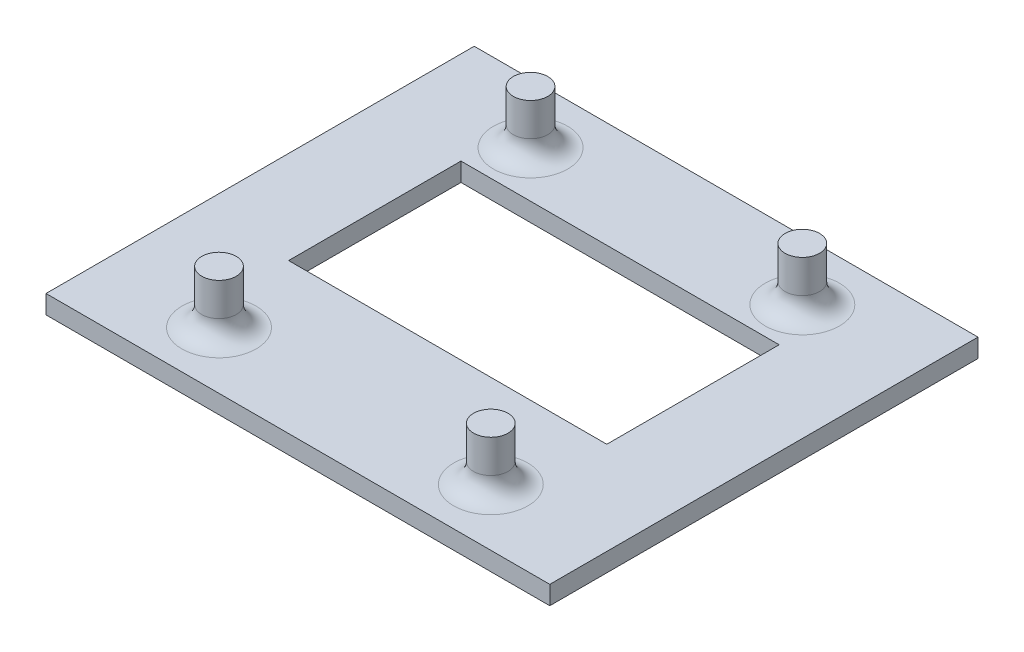
SolidWorks part; units mm, degrees
ref_plane "Front Plane" through (0, 0, 0) normal (0, 0, 1) x (1, 0, 0)
ref_plane "Top Plane" through (0, 0, 0) normal (0, 1, 0) x (1, 0, 0)
ref_plane "Right Plane" through (0, 0, 0) normal (1, 0, 0) x (0, 0, -1)
sketch "Sketch1" plane through (0, 0, 0) normal (0, 1, 0) x (1, 0, 0)
  line L0 (0, -55) -> (0, 55) construction
  line L1 (12, -6.5) -> (-12, -6.5)
  line L2 (12, -6.5) -> (12, 6.5)
  line L3 (12, 6.5) -> (-12, 6.5)
  line L4 (-12, -6.5) -> (-12, 6.5)
  line L5 (12, -6.5) -> (-12, 6.5) construction
  line L6 (12, 6.5) -> (-12, -6.5) construction
  line L7 (19, -17.8) -> (-19, -17.8)
  line L8 (19, -17.8) -> (19, 14.5)
  line L9 (19, 14.5) -> (-19, 14.5)
  line L10 (-19, -17.8) -> (-19, 14.5)
  line L11 (19, -17.8) -> (-19, 14.5) construction
  line L12 (19, 14.5) -> (-19, -17.8) construction
  point P0 (0, 0)
  point P6 (0, -1.65)
  dimension "D1" = 24
  dimension "D2" = 13
  dimension "D3" = 38
  dimension "D4" = 11.3
  dimension "D5" = 8
extrude "Boss-Extrude1" add sketch "Sketch1" along normal blind 1.4
sketch "Sketch2" plane through (0, 1.4, 0) normal (0, 1, 0) x (1, 0, 0)
  line L0 (0, -0.77) -> (0, 0.77) construction
  line L1 (12, 6.5) -> (-12, 6.5) construction
  circle A0 centre (-10.25, 10) radius 1.3
  circle A1 centre (-10.25, -13.5) radius 1.3
  circle A2 centre (10.25, -13.5) radius 1.3
  circle A3 centre (10.25, 10) radius 1.3
  dimension "D1" = 10.25
  dimension "D2" = 23.5
  dimension "D3" = 3.5
extrude "Boss-Extrude2" add sketch "Sketch2" along normal blind 4
fillet "Fillet1" radius 1.5 4 edges at (-10.25, 1.4, 14.8) (10.25, 1.4, 12.2) (10.25, 1.4, -11.3) (-10.25, 1.4, -8.7)
